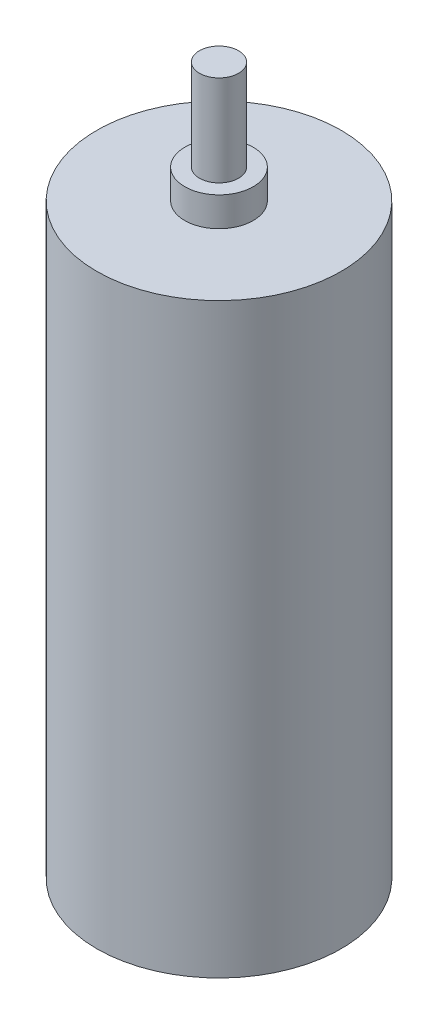
SolidWorks part; units mm, degrees
ref_plane "Front Plane" through (0, 0, 0) normal (0, 0, 1) x (1, 0, 0)
ref_plane "Top Plane" through (0, 0, 0) normal (0, 1, 0) x (1, 0, 0)
ref_plane "Right Plane" through (0, 0, 0) normal (1, 0, 0) x (0, 0, -1)
sketch "Sketch1" plane through (0, 0, 0) normal (0, 1, 0) x (1, 0, 0)
  circle A0 centre (0, 0) radius 12.5
  point P3 (0, 0)
  dimension "D1" = 25
extrude "Boss-Extrude1" add sketch "Sketch1" against normal blind 60 contours A0
sketch "Sketch2" plane through (0, 0, 0) normal (0, 1, 0) x (1, 0, 0)
  circle A0 centre (0, 0) radius 3.5
  dimension "D1" = 7
extrude "Boss-Extrude2" add sketch "Sketch2" along normal blind 3
sketch "Sketch3" plane through (0, 3, 0) normal (0, 1, 0) x (1, 0, 0)
  circle A0 centre (0, 0) radius 2
  dimension "D1" = 4
extrude "Boss-Extrude3" add sketch "Sketch3" along normal blind 9.3
